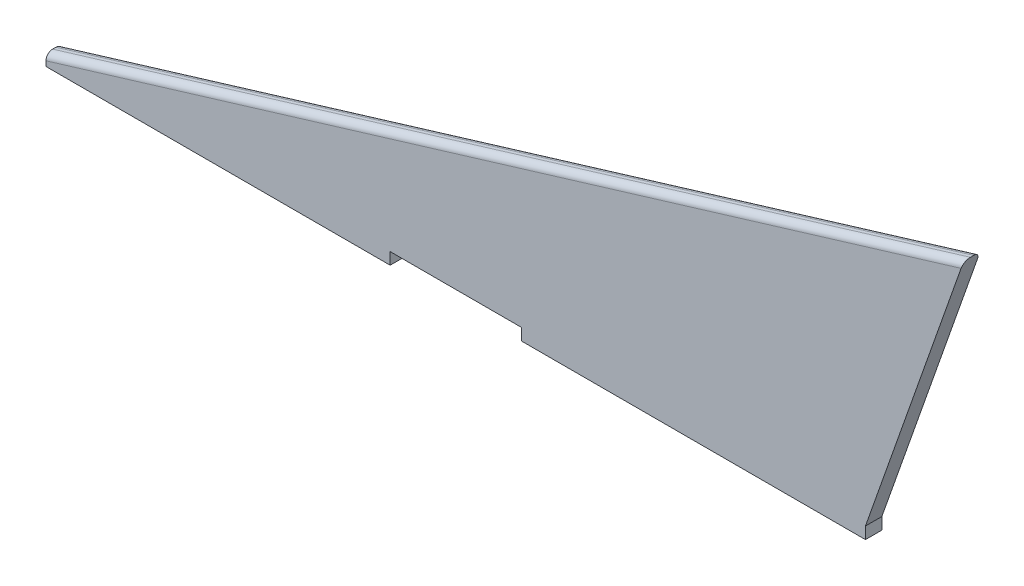
SolidWorks part; units mm, degrees
ref_plane "Front Plane" through (0, 0, 0) normal (0, 0, 1) x (1, 0, 0)
ref_plane "Top Plane" through (0, 0, 0) normal (0, 1, 0) x (1, 0, 0)
ref_plane "Right Plane" through (0, 0, 0) normal (1, 0, 0) x (0, 0, -1)
sketch "Sketch1" plane through (0, 0, 0) normal (0, 0, 1) x (1, 0, 0)
  line L0 (0, 0) -> (140, 42.5)
  line L1 (140, 42.5) -> (125, 0)
  line L2 (72.5, 0) -> (52.5, 0)
  line L5 (0, 0) -> (0, -1.8)
  line L6 (0, -1.8) -> (52.5, -1.8)
  line L7 (52.5, 0) -> (52.5, -1.8)
  line L9 (72.5, 0) -> (72.5, -1.8)
  line L10 (72.5, -1.8) -> (125, -1.8)
  line L11 (125, 0) -> (125, -1.8)
  point P12 (0, 0)
  dimension "D1" = 125
  dimension "D2" = 42.5
  dimension "D3" = 140
  dimension "D4" = 20
  dimension "D5" = 1.8
  dimension "D6" = 52.5
extrude "Boss-Extrude1" add sketch "Sketch1" along normal blind 2.5
fillet "Fillet1" radius 1 2 edges at (70, 21.25, 0) (70, 21.25, 2.5)
